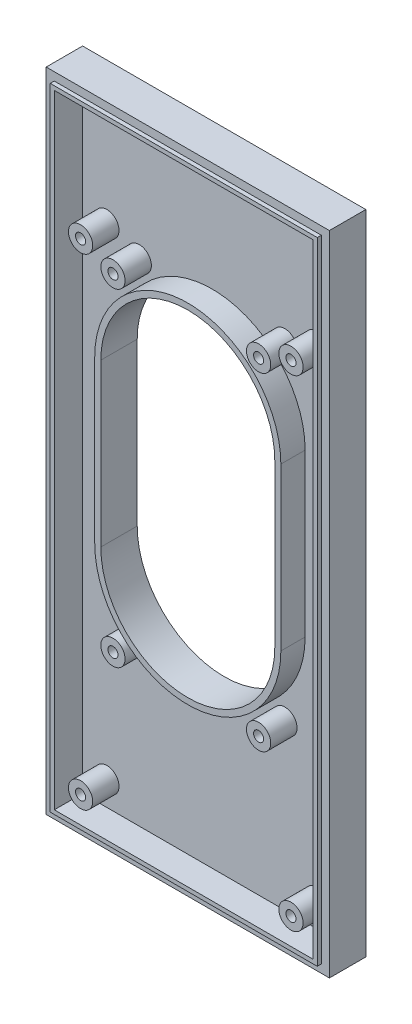
SolidWorks part; units mm, degrees
material "ABS"
ref_plane "Alzado" through (0, 0, 0) normal (0, 0, 1) x (1, 0, 0)
ref_plane "Planta" through (0, 0, 0) normal (0, 1, 0) x (1, 0, 0)
ref_plane "Vista lateral" through (0, 0, 0) normal (1, 0, 0) x (0, 0, -1)
sketch "Croquis1" plane through (0, 0, 0) normal (0, 0, 1) x (1, 0, 0)
  line L1 (0, 0) -> (70, 0)
  line L2 (0, 0) -> (0, 160)
  line L3 (0, 160) -> (70, 160)
  line L4 (70, 0) -> (70, 160)
  dimension "D1" = 70
  dimension "D2" = 160
extrude "Saliente-Extruir1" add sketch "Croquis1" against normal blind 10
shell "Vaciado1" thickness 3
sketch "Croquis2" plane through (0, 0, 0) normal (0, 0, 1) x (1, 0, 0)
  line L0 (0, 0) -> (70, 0) construction
  line L1 (2, 2) -> (68, 2)
  line L2 (2, 2) -> (2, 158)
  line L3 (2, 158) -> (68, 158)
  line L4 (68, 2) -> (68, 158)
  line L5 (0, 160) -> (0, 0) construction
  line L7 (0, 160) -> (70, 160)
  line L8 (0, 160) -> (0, 0)
  line L9 (0, 0) -> (70, 0)
  line L10 (70, 160) -> (70, 0)
  dimension "D1" = 66
  dimension "D2" = 156
  dimension "D3" = 2
  dimension "D4" = 2
  dimension "D5" = 70
  dimension "D6" = 160
extrude "Cortar-Extruir1" cut sketch "Croquis2" against normal blind 1
sketch "Croquis3" plane through (0, 0, -7) normal (0, 0, 1) x (1, 0, 0)
  line L0 (35, 157) -> (35, 43.2994) construction
  line L1 (67, 157) -> (3, 157) construction
  line L2 (35, 104) -> (35, 64) construction
  line L3 (58, 104) -> (58, 64)
  line L4 (12, 104) -> (12, 64)
  line L5 (67, 157) -> (3, 157) construction
  line L6 (35, 104) -> (35, 64) construction
  line L7 (56.5, 104) -> (56.5, 64)
  line L8 (13.5, 104) -> (13.5, 64)
  arc A0 (58, 104) -> (12, 104) centre (35, 104) ccw
  arc A1 (12, 64) -> (58, 64) centre (35, 64) ccw
  arc A2 (56.5, 104) -> (13.5, 104) centre (35, 104) ccw
  arc A3 (13.5, 64) -> (56.5, 64) centre (35, 64) ccw
  point P6 (35, 84)
  point P11 (35, 127)
  point P12 (35, 41)
  point P17 (35, 84)
  dimension "D2" = 30
  dimension "D1" = 86
  dimension "D3" = 46
  dimension "D4" = 43
extrude "Saliente-Extruir2" add sketch "Croquis3" along normal blind 6
sketch "Croquis4" plane through (0, 0, -7) normal (0, 0, 1) x (1, 0, 0)
  line L0 (35, 104) -> (35, 64) construction
  line L1 (56.5, 104) -> (56.5, 64)
  line L2 (13.5, 104) -> (13.5, 64)
  arc A0 (56.5, 104) -> (13.5, 104) centre (35, 104) ccw
  arc A1 (13.5, 64) -> (56.5, 64) centre (35, 64) ccw
  point P4 (35, 84)
  dimension "D1" = 43
extrude "Cortar-Extruir2" cut sketch "Croquis4" against normal blind 6
sketch "Croquis5" plane through (0, 0, -7) normal (0, 0, 1) x (1, 0, 0)
  line L0 (12, 128.5) -> (58, 128.5) construction
  line L1 (58, 128.5) -> (58, 39.5) construction
  line L2 (58, 39.5) -> (12, 39.5) construction
  line L3 (12, 39.5) -> (12, 128.5) construction
  line L4 (12, 104) -> (12, 64) construction
  arc A0 (58, 104) -> (12, 104) centre (35, 104) ccw construction
  arc A1 (12, 64) -> (58, 64) centre (35, 64) ccw construction
  circle A2 centre (17, 124.5) radius 3
  circle A3 centre (53, 124.5) radius 3
  circle A4 centre (17, 43.5) radius 3
  circle A5 centre (53, 43.5) radius 3
  circle A6 centre (17, 124.5) radius 1.25
  circle A7 centre (53, 124.5) radius 1.25
  circle A8 centre (17, 43.5) radius 1.25
  circle A9 centre (53, 43.5) radius 1.25
  point P7 (35, 127)
  point P8 (35, 39.5)
  point P12 (35, 41)
  dimension "D4" = 6
  dimension "D6" = 5
  dimension "D7" = 4
  dimension "D9" = 4
  dimension "D10" = 5
  dimension "D12" = 4
  dimension "D13" = 2.5
  dimension "D1" = 1.5
  dimension "D2" = 1.5
  dimension "D3" = 46
  dimension "D5" = 4
  dimension "D8" = 5
  dimension "D11" = 5
extrude "Saliente-Extruir3" add sketch "Croquis5" along normal blind 6.5
sketch "Croquis6" plane through (0, 0, -7) normal (0, 0, 1) x (1, 0, 0)
  line L0 (2, 158) -> (2, 2) construction
  line L2 (68, 2) -> (68, 158) construction
  line L5 (68, 158) -> (2, 158) construction
  line L6 (0, 0) -> (70, 0) construction
  circle A0 centre (9, 9) radius 3
  circle A1 centre (9, 9) radius 1.25
  circle A2 centre (61, 9) radius 3
  circle A3 centre (61, 9) radius 1.25
  circle A4 centre (9, 128) radius 3
  circle A5 centre (9, 128) radius 1.25
  circle A6 centre (61, 128) radius 3
  circle A7 centre (61, 128) radius 1.25
  dimension "D1" = 6
  dimension "D4" = 2.5
  dimension "D7" = 7
  dimension "D2" = 7
  dimension "D3" = 9
  dimension "D5" = 7
  dimension "D6" = 9
  dimension "D8" = 30
  dimension "D9" = 30
  dimension "D10" = 7
extrude "Saliente-Extruir4" add sketch "Croquis6" along normal blind 6.5
